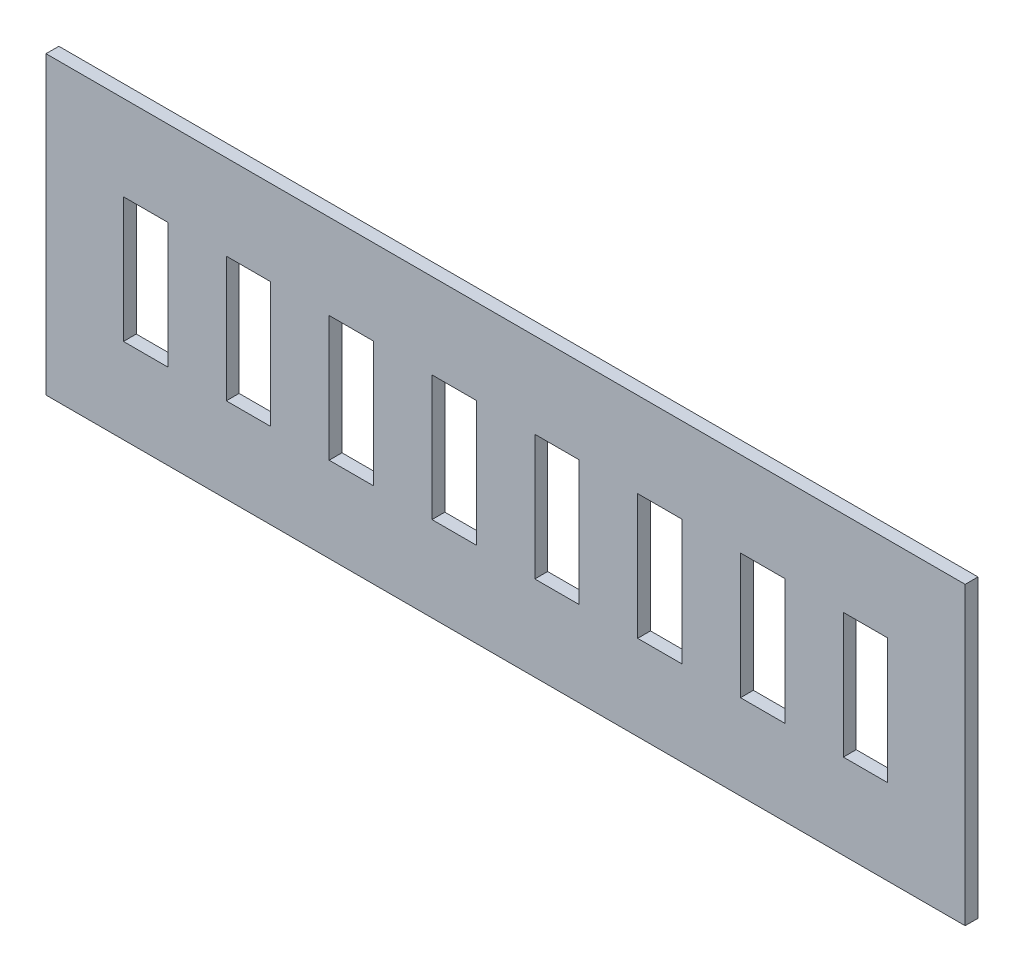
SolidWorks part; units mm, degrees
ref_plane "Front Plane" through (0, 0, 0) normal (0, 0, 1) x (1, 0, 0)
ref_plane "Top Plane" through (0, 0, 0) normal (0, 1, 0) x (1, 0, 0)
ref_plane "Right Plane" through (0, 0, 0) normal (1, 0, 0) x (0, 0, -1)
sketch "Sketch1" plane through (0, 0, 0) normal (0, 0, 1) x (1, 0, 0)
  line L0 (0, 641.0725) -> (0, -660.9336) construction
  line L1 (-1180.6327, 0) -> (1118.8426, 0) construction
  line L2 (-434.5, 97.5) -> (-365.5, 97.5)
  line L3 (-715, 230) -> (715, 230)
  line L4 (-715, 230) -> (-715, -230)
  line L5 (-715, -230) -> (715, -230)
  line L6 (715, 230) -> (715, -230)
  line L7 (-715, 230) -> (715, -230) construction
  line L8 (-715, -230) -> (715, 230) construction
  line L9 (-594.5, 97.5) -> (-525.5, 97.5)
  line L10 (-594.5, 97.5) -> (-594.5, -97.5)
  line L11 (-594.5, -97.5) -> (-525.5, -97.5)
  line L12 (-525.5, 97.5) -> (-525.5, -97.5)
  line L13 (-594.5, 97.5) -> (-525.5, -97.5) construction
  line L14 (-594.5, -97.5) -> (-525.5, 97.5) construction
  line L15 (-365.5, 97.5) -> (-365.5, -97.5)
  line L16 (-434.5, -97.5) -> (-365.5, -97.5)
  line L17 (-434.5, 97.5) -> (-434.5, -97.5)
  line L18 (-274.5, 97.5) -> (-205.5, 97.5)
  line L19 (-205.5, 97.5) -> (-205.5, -97.5)
  line L20 (-274.5, -97.5) -> (-205.5, -97.5)
  line L21 (-274.5, 97.5) -> (-274.5, -97.5)
  line L22 (-114.5, 97.5) -> (-45.5, 97.5)
  line L23 (-45.5, 97.5) -> (-45.5, -97.5)
  line L24 (-114.5, -97.5) -> (-45.5, -97.5)
  line L25 (-114.5, 97.5) -> (-114.5, -97.5)
  line L26 (45.5, 97.5) -> (114.5, 97.5)
  line L27 (114.5, 97.5) -> (114.5, -97.5)
  line L28 (45.5, -97.5) -> (114.5, -97.5)
  line L29 (45.5, 97.5) -> (45.5, -97.5)
  line L30 (205.5, 97.5) -> (274.5, 97.5)
  line L31 (274.5, 97.5) -> (274.5, -97.5)
  line L32 (205.5, -97.5) -> (274.5, -97.5)
  line L33 (205.5, 97.5) -> (205.5, -97.5)
  line L34 (365.5, 97.5) -> (434.5, 97.5)
  line L35 (434.5, 97.5) -> (434.5, -97.5)
  line L36 (365.5, -97.5) -> (434.5, -97.5)
  line L37 (365.5, 97.5) -> (365.5, -97.5)
  line L38 (525.5, 97.5) -> (594.5, 97.5)
  line L39 (594.5, 97.5) -> (594.5, -97.5)
  line L40 (525.5, -97.5) -> (594.5, -97.5)
  line L41 (525.5, 97.5) -> (525.5, -97.5)
  line L42 (560, 125.0794) -> (560, -146.0947) construction
  point P5 (0, 0)
  point P10 (-560, 0)
  dimension "D1" = 1430
  dimension "D2" = 460
  dimension "D3" = 69
  dimension "D4" = 195
  dimension "D5" = 155
  dimension "D7" = 34.5
  dimension "D8" = 160
  dimension "D9" = 160
  dimension "D10" = 160
  dimension "D11" = 160
  dimension "D12" = 160
  dimension "D13" = 160
  dimension "D14" = 160
  dimension "D15" = 155
  dimension "D6" = 8
extrude "Boss-Extrude1" add sketch "Sketch1" along normal blind 20
